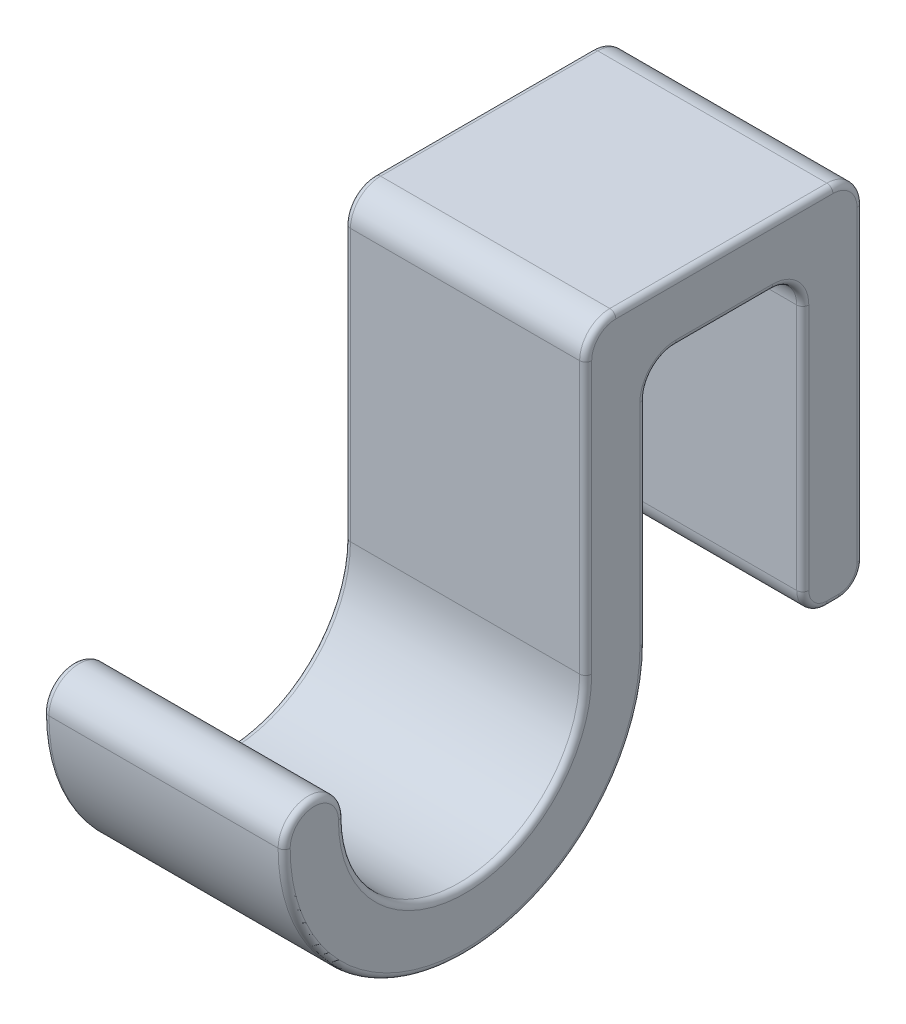
SolidWorks part; units mm, degrees
ref_plane "Front Plane" through (0, 0, 0) normal (0, 0, 1) x (1, 0, 0)
ref_plane "Top Plane" through (0, 0, 0) normal (0, 1, 0) x (1, 0, 0)
ref_plane "Right Plane" through (0, 0, 0) normal (1, 0, 0) x (0, 0, -1)
sketch "Sketch1" plane through (0, 0, 0) normal (1, 0, 0) x (0, 0, -1)
  line L0 (0, 0) -> (0, 22.5)
  line L1 (5, 0) -> (5, 17.5)
  line L4 (5, 0) -> (5, 25) construction
  line L7 (2.5, 25) -> (20.5, 25)
  line L8 (23, 22.5) -> (23, -3)
  line L9 (21, -5) -> (20, -5)
  line L10 (18, -3) -> (18, 17.5)
  line L11 (15.5, 20) -> (7.5, 20)
  line L12 (0, 0) -> (0, 25) construction
  arc A0 (-20, 0) -> (0, 0) centre (-10, 0) ccw
  arc A1 (-25, 0) -> (5, 0) centre (-10, 0) ccw
  arc A2 (-20, 0) -> (-25, 0) centre (-22.5, 0) ccw
  arc A3 (23, 22.5) -> (20.5, 25) centre (20.5, 22.5) ccw
  arc A4 (18, 17.5) -> (15.5, 20) centre (15.5, 17.5) ccw
  arc A5 (5, 17.5) -> (7.5, 20) centre (7.5, 17.5) cw
  arc A6 (0, 22.5) -> (2.5, 25) centre (2.5, 22.5) cw
  arc A7 (21, -5) -> (23, -3) centre (21, -3) ccw
  arc A8 (20, -5) -> (18, -3) centre (20, -3) cw
  point P11 (-10, -10)
  point P16 (5, 19.562)
  point P19 (23, 25)
  point P22 (18, 20)
  point P25 (5, 20)
  point P29 (0, 25)
  point P32 (23, -5)
  dimension "D6" = 30
  dimension "D7" = 13
  dimension "D8" = 2.5
  dimension "D9" = 2
  dimension "D1" = 20
  dimension "D2" = 25
  dimension "D4" = 5
  dimension "D5" = 5
  dimension "D3" = 5
extrude "Boss-Extrude1" add sketch "Sketch1" along normal blind 20 contours L0 A6 L7 A3 L8 A7 L9 A8 L10 A4 L11 A5 L1 A1 A2 A0
fillet "Fillet1" radius 0.5 32 edges at (0, -10, 10) (0, 2.5, 22.5) (0, -15, 10) (0, 8.75, -5) (20, -10, 10) (20, 2.5, 22.5) (20, -15, 10) (20, 8.75, -5) (0, 11.25, 0) (20, 11.25, 0) (0, 19.2678, -5.7322) (0, 20, -11.5) (0, 19.2678, -17.2678) (0, 7.25, -18) (0, -4.4142, -18.5858) (0, -5, -20.5) (0, -4.4142, -22.4142) (0, 9.75, -23) (0, 24.2678, -22.2678) (0, 25, -11.5) (0, 24.2678, -0.7322) (20, 19.2678, -5.7322) (20, 20, -11.5) (20, 19.2678, -17.2678) (20, 7.25, -18) (20, -4.4142, -18.5858) (20, -5, -20.5) (20, -4.4142, -22.4142) (20, 9.75, -23) (20, 24.2678, -22.2678) (20, 25, -11.5) (20, 24.2678, -0.7322)
